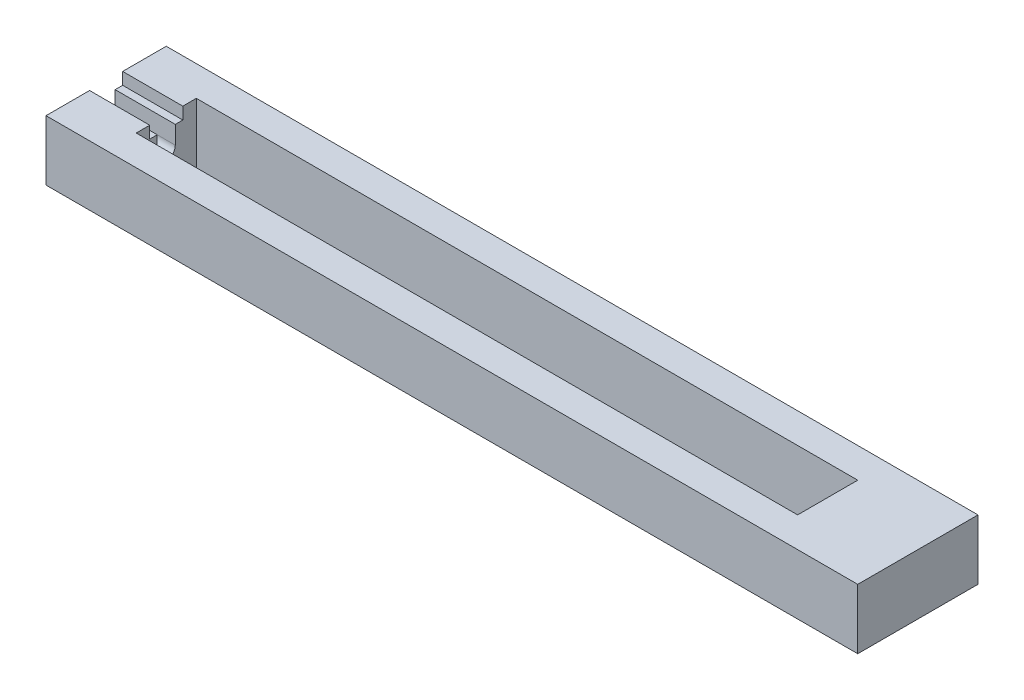
SolidWorks part; units mm, degrees
ref_plane "Front Plane" through (0, 0, 0) normal (0, 0, 1) x (1, 0, 0)
ref_plane "Top Plane" through (0, 0, 0) normal (0, 1, 0) x (1, 0, 0)
ref_plane "Right Plane" through (0, 0, 0) normal (1, 0, 0) x (0, 0, -1)
sketch "Sketch1" plane through (0, 0, 0) normal (0, 1, 0) x (1, 0, 0)
  line L1 (-6.75, -1) -> (6.75, -1)
  line L2 (-6.75, -1) -> (-6.75, 1)
  line L3 (-6.75, 1) -> (6.75, 1)
  line L4 (6.75, -1) -> (6.75, 1)
  line L5 (-6.75, -1) -> (6.75, 1) construction
  line L6 (-6.75, 1) -> (6.75, -1) construction
  line L7 (-5.75, 0.5) -> (5.25, 0.5)
  line L8 (-5.75, 0.5) -> (-5.75, -0.5)
  line L9 (-5.75, -0.5) -> (5.25, -0.5)
  line L10 (5.25, 0.5) -> (5.25, -0.5)
  point P0 (0, 0)
  point P6 (0, 0)
  dimension "D1" = 2
  dimension "D2" = 13.5
  dimension "D3" = 1
  dimension "D4" = 1.5
  dimension "D5" = 1
extrude "Boss-Extrude1" add sketch "Sketch1" along normal blind 1
sketch "Sketch2" plane through (-6.75, 0, 0) normal (-1, 0, 0) x (0, 0, 1)
  line L0 (0.15, 0.8) -> (0.275, 0.8)
  line L1 (-1, 1) -> (1, 1) construction
  line L3 (0.15, 0.5) -> (0.15, 0.8)
  line L4 (0.15, 1) -> (-0.15, 1)
  line L5 (1, 1) -> (1, 0) construction
  line L6 (-0.15, 0.5) -> (-0.15, 0.8)
  line L7 (-1, 0) -> (1, 0) construction
  line L9 (-0.275, 0.8) -> (-0.15, 0.8)
  line L10 (-0.275, 0.8) -> (-0.275, 1)
  line L11 (-0.275, 1) -> (0.275, 1)
  line L12 (0.275, 0.8) -> (0.275, 1)
  arc A0 (-0.15, 0.5) -> (0.15, 0.5) centre (0, 0.5) ccw
  point P12 (0, 0.9)
  line M3 (1, 1) -> (-1, 1)
  dimension "D1" = 0.55
  dimension "D2" = 0.2
  dimension "D3" = 1
  dimension "D4" = 0
  dimension "D5" = 0.5
extrude "Cut-Extrude2" cut sketch "Sketch2" against normal blind 1 contours L6 A0 L3 L0 L12 L10 L9 M3
ref_plane "Plane1" through (0, 0.5, 0) normal (0, -1, 0) x (-1, 0, 0)
